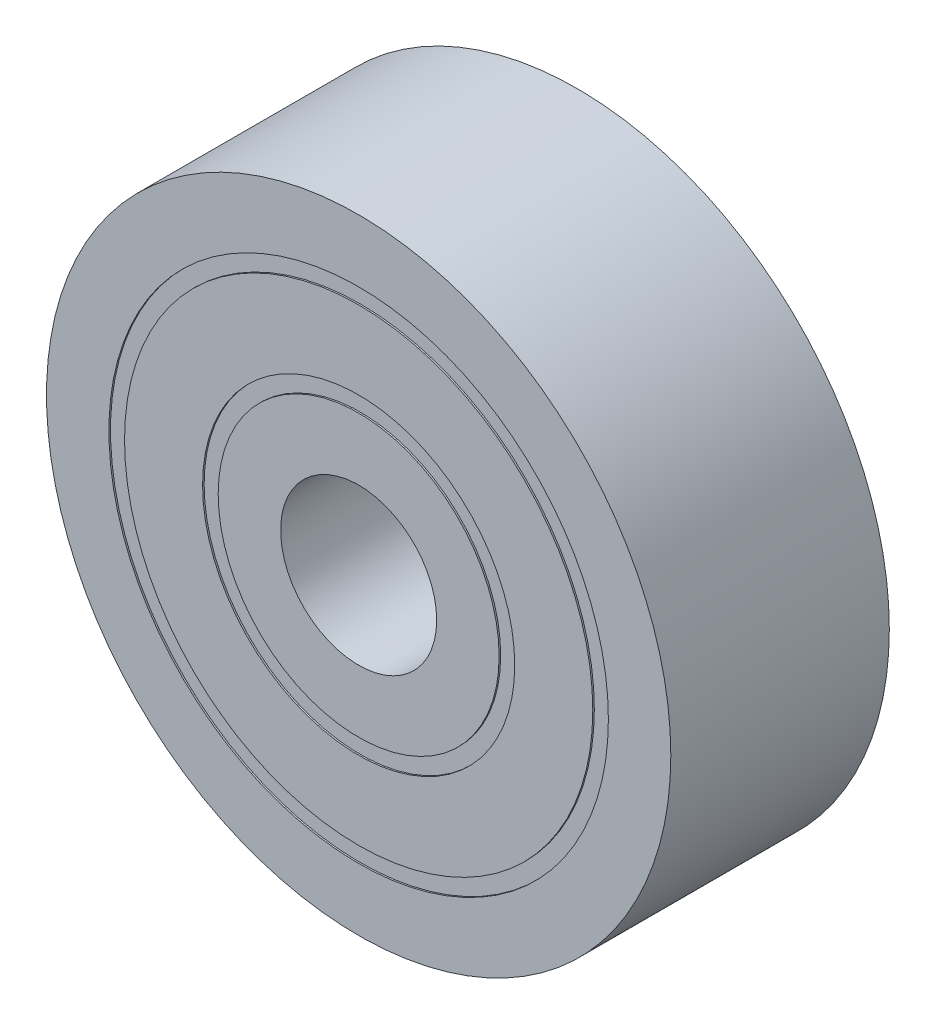
SolidWorks part; units mm, degrees
material "ASTM A36 Aço"
ref_plane "Plano frontal" through (0, 0, 0) normal (0, 0, 1) x (1, 0, 0)
ref_plane "Plano superior" through (0, 0, 0) normal (0, 1, 0) x (1, 0, 0)
ref_plane "Plano direito" through (0, 0, 0) normal (1, 0, 0) x (0, 0, -1)
sketch "Esboço1" plane through (0, 0, 0) normal (0, 0, 1) x (1, 0, 0)
  circle A0 centre (0, 0) radius 12.5
  circle A1 centre (0, 0) radius 50
  dimension "D1" = 25
  dimension "D2" = 100
extrude "Ressalto-extrusão1" add sketch "Esboço1" along normal mid plane 35
sketch "Esboço2" plane through (0, 0, 17.5) normal (0, 0, 1) x (1, 0, 0)
  circle A0 centre (0, 0) radius 40
  circle A1 centre (0, 0) radius 50
  circle A2 centre (0, 0) radius 50
  circle A3 centre (0, 0) radius 37.5
  circle A4 centre (0, 0) radius 25
  circle A5 centre (0, 0) radius 22.5
  circle A6 centre (0, 0) radius 22.5
  dimension "D1" = 0
  dimension "D2" = 10
  dimension "D3" = 2.5
  dimension "D4" = 10
  dimension "D5" = 2.5
extrude "Corte-extrusão1" cut sketch "Esboço2" against normal blind 0.25 contours A4 A6 | A0 A3
mirror "Espelhar1" about plane through (0, 0, 0) normal (0, 0, 1) of "Corte-extrusão1"
